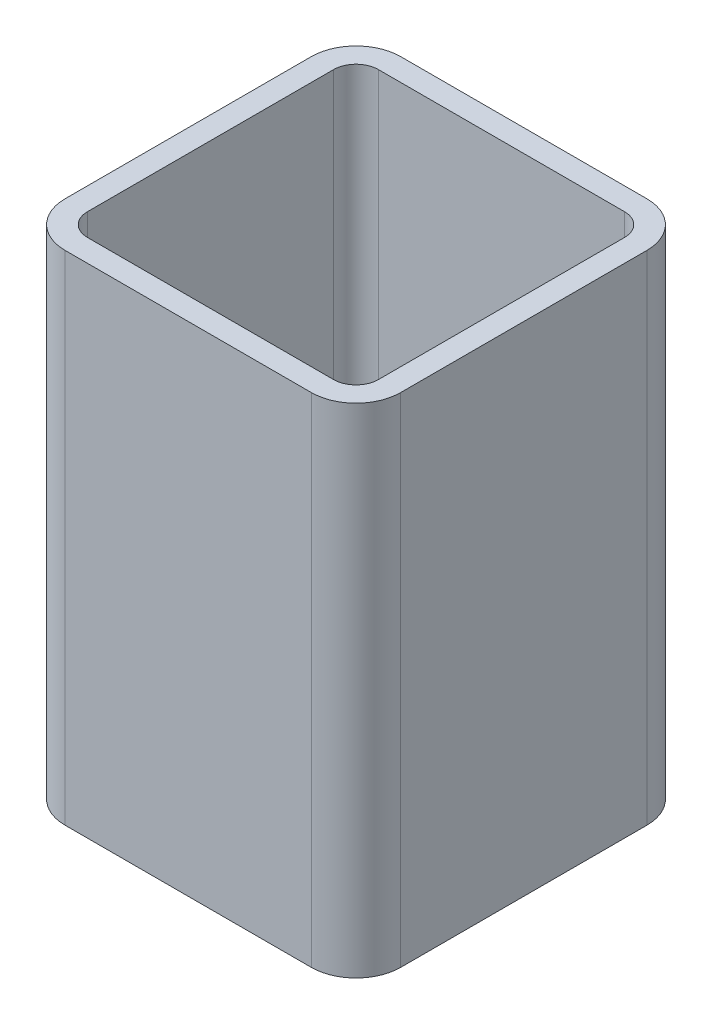
SolidWorks part; units mm, degrees
ref_plane "前视基准面" through (0, 0, 0) normal (0, 0, 1) x (1, 0, 0)
ref_plane "上视基准面" through (0, 0, 0) normal (0, 1, 0) x (1, 0, 0)
ref_plane "右视基准面" through (0, 0, 0) normal (1, 0, 0) x (0, 0, -1)
sketch "草图1" plane through (0, 0, 0) normal (0, 1, 0) x (1, 0, 0)
  line L0 (-11, -13) -> (11, -13)
  line L1 (-11, -15) -> (11, -15)
  line L2 (-15, -11) -> (-15, 11)
  line L3 (-11, 15) -> (11, 15)
  line L4 (15, -11) -> (15, 11)
  line L5 (13, -11) -> (13, 11)
  line L6 (-11, 13) -> (11, 13)
  line L7 (-13, -11) -> (-13, 11)
  arc A0 (-11, -15) -> (-15, -11) centre (-11, -11) cw
  arc A1 (11, -15) -> (15, -11) centre (11, -11) ccw
  arc A2 (11, 15) -> (15, 11) centre (11, 11) cw
  arc A3 (-15, 11) -> (-11, 15) centre (-11, 11) cw
  arc A4 (11, -13) -> (13, -11) centre (11, -11) ccw
  arc A5 (11, 13) -> (13, 11) centre (11, 11) cw
  arc A6 (-13, 11) -> (-11, 13) centre (-11, 11) cw
  arc A7 (-11, -13) -> (-13, -11) centre (-11, -11) cw
extrude "凸台-拉伸1" add sketch "草图1" along normal blind 44.5
